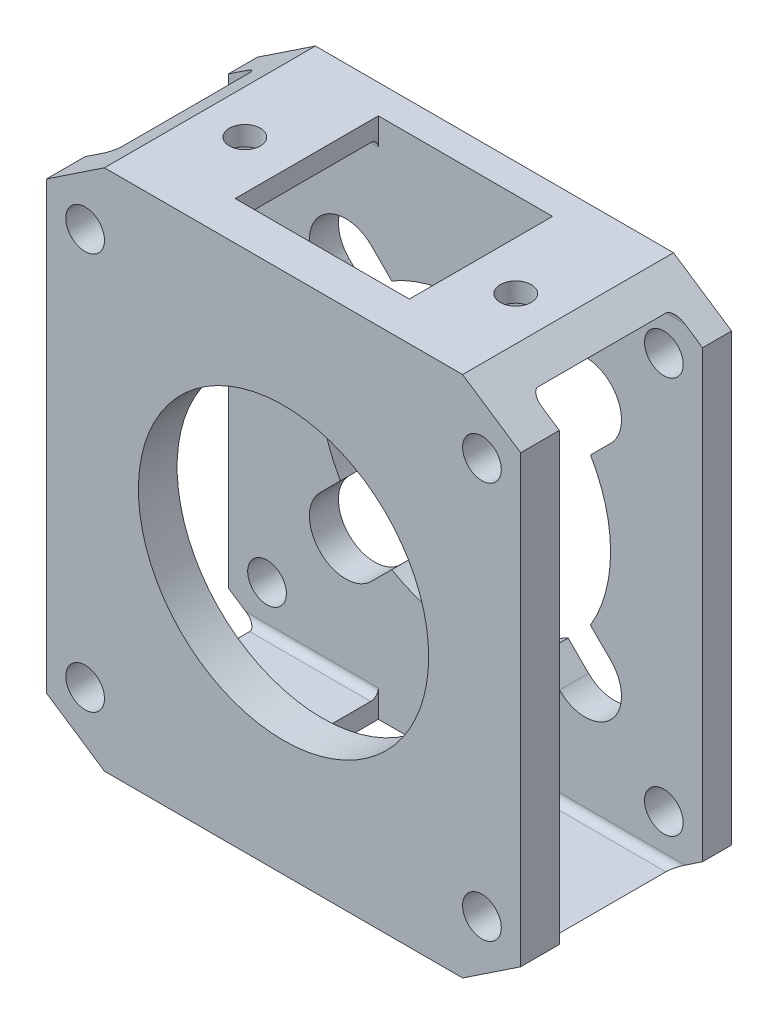
SolidWorks part; units mm, degrees
material "6061 合金"
ref_plane "前视基准面" through (0, 0, 0) normal (0, 0, 1) x (1, 0, 0)
ref_plane "上视基准面" through (0, 0, 0) normal (0, 1, 0) x (1, 0, 0)
ref_plane "右视基准面" through (0, 0, 0) normal (1, 0, 0) x (0, 0, -1)
sketch "草图1" plane through (0, 0, 0) normal (0, 0, 1) x (1, 0, 0)
  line L0 (0, 75.9619) -> (0, -69.4948) construction
  line L1 (-64.9435, 0) -> (83.5981, 0) construction
  line L2 (0, 0) -> (-29.9259, 29.9259) construction
  line L7 (-24.5061, 23.0061) -> (-18.5061, 27.0061)
  line L8 (-18.5061, 27.0061) -> (18.5061, 27.0061)
  line L9 (-24.5061, 23.0061) -> (-24.5061, -23.0061)
  line L10 (-18.5061, -27.0061) -> (18.5061, -27.0061)
  line L11 (24.5061, 23.0061) -> (24.5061, -23.0061)
  line L12 (18.5061, 27.0061) -> (24.5061, 23.0061)
  line L13 (-24.5061, -23.0061) -> (-18.5061, -27.0061)
  line L14 (18.5061, -27.0061) -> (24.5061, -23.0061)
  circle A1 centre (0, 0) radius 15
  circle A2 centre (-20.5061, 20.5061) radius 2
  circle A3 centre (20.5061, 20.5061) radius 2
  circle A4 centre (20.5061, -20.5061) radius 2
  circle A5 centre (-20.5061, -20.5061) radius 2
  point P12 (-24.5061, 27.0061)
  point P19 (0, 0)
  point P20 (24.5061, -27.0061)
  point P21 (-24.5061, -27.0061)
  point P22 (24.5061, 27.0061)
  dimension "D1" = 29
  dimension "D2" = 30
  dimension "D3" = 4
  dimension "D4" = 45
  dimension "D6" = 6.5
  dimension "D7" = 4
  dimension "D8" = 6.5
  dimension "D9" = 6
  dimension "D10" = 4
  dimension "D11" = 6
  dimension "D12" = 4
  dimension "D13" = 4
  dimension "D14" = 6
  dimension "D15" = 6
  dimension "D16" = 4
  dimension "D5" = 4
extrude "凸台-拉伸1" add sketch "草图1" along normal blind 21.8
sketch "草图2" plane through (-24.5061, 0, 0) normal (-1, 0, 0) x (0, 0, 1)
  line L0 (21.8, 23.0061) -> (21.8, -23.0061) construction
  line L1 (3, 25.0061) -> (17.8, 25.0061)
  line L2 (3, 25.0061) -> (3, -25.0061)
  line L3 (3, -25.0061) -> (17.8, -25.0061)
  line L4 (17.8, 25.0061) -> (17.8, -25.0061)
  line L5 (0, 23.0061) -> (0, -23.0061) construction
  line L6 (21.8, 27.0061) -> (0, 27.0061) construction
  line L7 (21.8, -27.0061) -> (0, -27.0061) construction
  dimension "D1" = 4
  dimension "D2" = 3
  dimension "D3" = 2
  dimension "D4" = 2
extrude "切除-拉伸1" cut sketch "草图2" against normal through all
fillet "圆角1" radius 0.8 4 edges at (0, -25.0061, 3) (0, -25.0061, 17.8) (0, 25.0061, 17.8) (0, 25.0061, 3)
sketch "草图3" plane through (0, 27.0061, 0) normal (0, 1, 0) x (1, 0, 0)
  line L0 (0, 0) -> (0, -29.337) construction
  line L1 (18.5061, -21.8) -> (-18.5061, -21.8) construction
  line L2 (18.5061, 0) -> (-18.5061, 0) construction
  circle A0 centre (-14, -11.8) radius 1.6
  circle A1 centre (14, -11.8) radius 1.6
  dimension "D1" = 3.2
  dimension "D2" = 28
  dimension "D3" = 10
  dimension "D4" = 11.8
extrude "切除-拉伸2" cut sketch "草图3" against normal through all
sketch "草图4" plane through (0, 27.0061, 0) normal (0, 1, 0) x (1, 0, 0)
  line L0 (0, 0) -> (0, -34.8902) construction
  line L1 (22.7061, -3) -> (24.5061, -3) construction
  line L2 (-9, -17.8) -> (9, -17.8)
  line L3 (-9, -17.8) -> (-9, -3)
  line L4 (-9, -3) -> (9, -3)
  line L5 (9, -17.8) -> (9, -3)
  line L6 (-9, -17.8) -> (9, -3) construction
  line L7 (-9, -3) -> (9, -17.8) construction
  line L8 (24.5061, -17.8) -> (22.7061, -17.8) construction
  circle A1 centre (14, -11.8) radius 1.6 construction
  point P3 (0, -10.4)
  dimension "D1" = 5
extrude "切除-拉伸3" cut sketch "草图4" against normal through all
sketch "草图5" plane through (0, 0, 0) normal (0, 0, -1) x (-1, 0, 0)
  line L0 (0, 0) -> (-30.9671, 30.9671) construction
  line L1 (0, 0) -> (0, 31.0955) construction
  line L2 (-15.026, 9.7227) -> (-12.9214, 7.6181)
  line L3 (-9.7227, 15.026) -> (-7.6181, 12.9214)
  line L4 (15.026, 9.7227) -> (12.9214, 7.6181)
  line L5 (9.7227, 15.026) -> (7.6181, 12.9214)
  line L6 (9.7227, -15.026) -> (7.6181, -12.9214)
  line L7 (15.026, -9.7227) -> (12.9214, -7.6181)
  line L8 (-15.026, -9.7227) -> (-12.9214, -7.6181)
  line L9 (-9.7227, -15.026) -> (-7.6181, -12.9214)
  arc A0 (-9.7227, 15.026) -> (-15.026, 9.7227) centre (-12.3744, 12.3744) ccw
  circle A1 centre (0, 0) radius 15 construction
  arc A2 (-7.6181, 12.9214) -> (-12.9214, 7.6181) centre (0, 0) ccw
  arc A3 (12.9214, 7.6181) -> (7.6181, 12.9214) centre (0, 0) ccw
  arc A4 (15.026, 9.7227) -> (9.7227, 15.026) centre (12.3744, 12.3744) ccw
  arc A5 (7.6181, -12.9214) -> (12.9214, -7.6181) centre (0, 0) ccw
  arc A6 (9.7227, -15.026) -> (15.026, -9.7227) centre (12.3744, -12.3744) ccw
  arc A7 (-12.9214, -7.6181) -> (-7.6181, -12.9214) centre (0, 0) ccw
  arc A8 (-15.026, -9.7227) -> (-9.7227, -15.026) centre (-12.3744, -12.3744) ccw
  circle A9 centre (0, 0) radius 22 construction
  point P28 (0, 0)
  dimension "D2" = 17.5
  dimension "D3" = 7.5
  dimension "D5" = 44
  dimension "D1" = 45
  dimension "D4" = 4
extrude "切除-拉伸4" cut sketch "草图5" against normal up to surface (3 mm away) up to face at (0, 15, 3)
